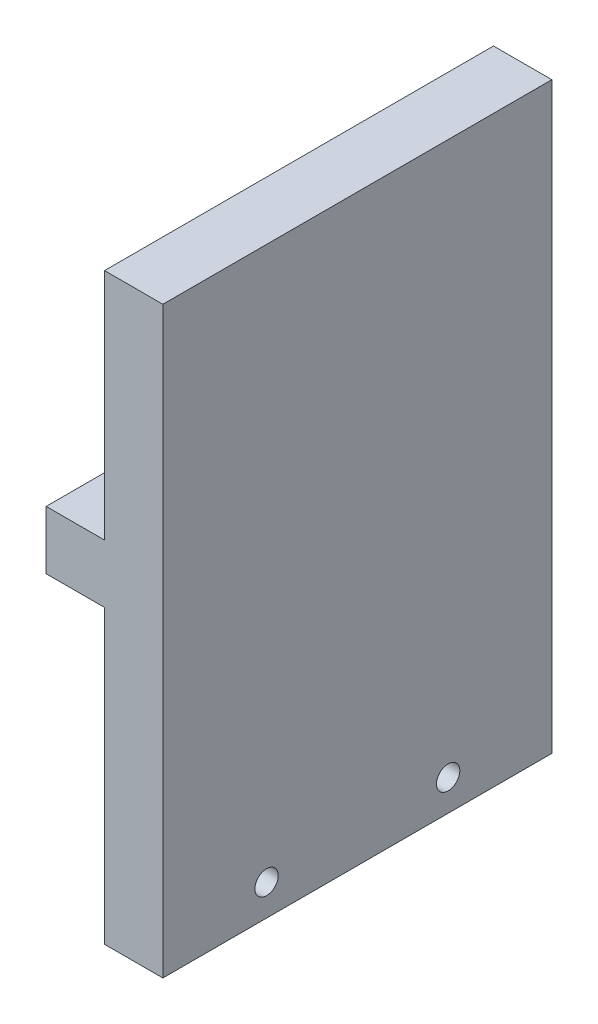
SolidWorks part; units mm, degrees
ref_plane "Alzado" through (0, 0, 0) normal (0, 0, 1) x (1, 0, 0)
ref_plane "Planta" through (0, 0, 0) normal (0, 1, 0) x (1, 0, 0)
ref_plane "Vista lateral" through (0, 0, 0) normal (1, 0, 0) x (0, 0, -1)
sketch "Croquis1" plane through (0, 0, 0) normal (1, 0, 0) x (0, 0, -1)
  line L1 (-50, -75) -> (50, -75)
  line L2 (-50, -75) -> (-50, 75)
  line L3 (-50, 75) -> (50, 75)
  line L4 (50, -75) -> (50, 75)
  line L5 (-50, -75) -> (50, 75) construction
  line L6 (-50, 75) -> (50, -75) construction
  point P0 (0, 0)
  dimension "D1" = 150
  dimension "D2" = 100
extrude "Saliente-Extruir1" add sketch "Croquis1" along normal blind 15
sketch "Croquis2" plane through (0, 0, 0) normal (-1, 0, 0) x (0, 0, 1)
  line L0 (50, 75) -> (50, -75) construction
  line L1 (50, 0) -> (15, 0)
  line L2 (50, 0) -> (50, 15)
  line L3 (50, 15) -> (15, 15)
  line L4 (15, 0) -> (15, 15)
  line L5 (-50, -75) -> (-50, 75) construction
  line L6 (-50, 0) -> (-15, 0)
  line L7 (-50, 0) -> (-50, -15)
  line L8 (-50, -15) -> (-15, -15)
  line L9 (-15, 0) -> (-15, -15)
  line L10 (-15, 0) -> (15, 0) construction
  dimension "D1" = 15
  dimension "D2" = 30
extrude "Saliente-Extruir2" add sketch "Croquis2" along normal blind 15
sketch "Croquis3" plane through (15, 0, 0) normal (1, 0, 0) x (0, 0, -1)
  line L0 (0, 75) -> (0, -75) construction
  line L1 (50, 75) -> (-50, 75) construction
  line L2 (-50, -75) -> (50, -75) construction
  line L3 (-23.345, -67) -> (0, -67) construction
  line L4 (0, -67) -> (23.345, -67) construction
  circle A0 centre (-23.345, -67) radius 3
  circle A1 centre (23.345, -67) radius 3
  dimension "D2" = 6
  dimension "D1" = 46.69
  dimension "D3" = 8
extrude "Cortar-Extruir1" cut sketch "Croquis3" against normal through all
sketch "Croquis4" plane through (15, 0, 0) normal (1, 0, 0) x (0, 0, -1)
  line L0 (-23.345, -70) -> (-23.345, -64) construction
  line L1 (23.345, -70) -> (23.345, -64) construction
  circle A0 centre (-23.345, -67) radius 3 construction
  circle A1 centre (23.345, -67) radius 3 construction
